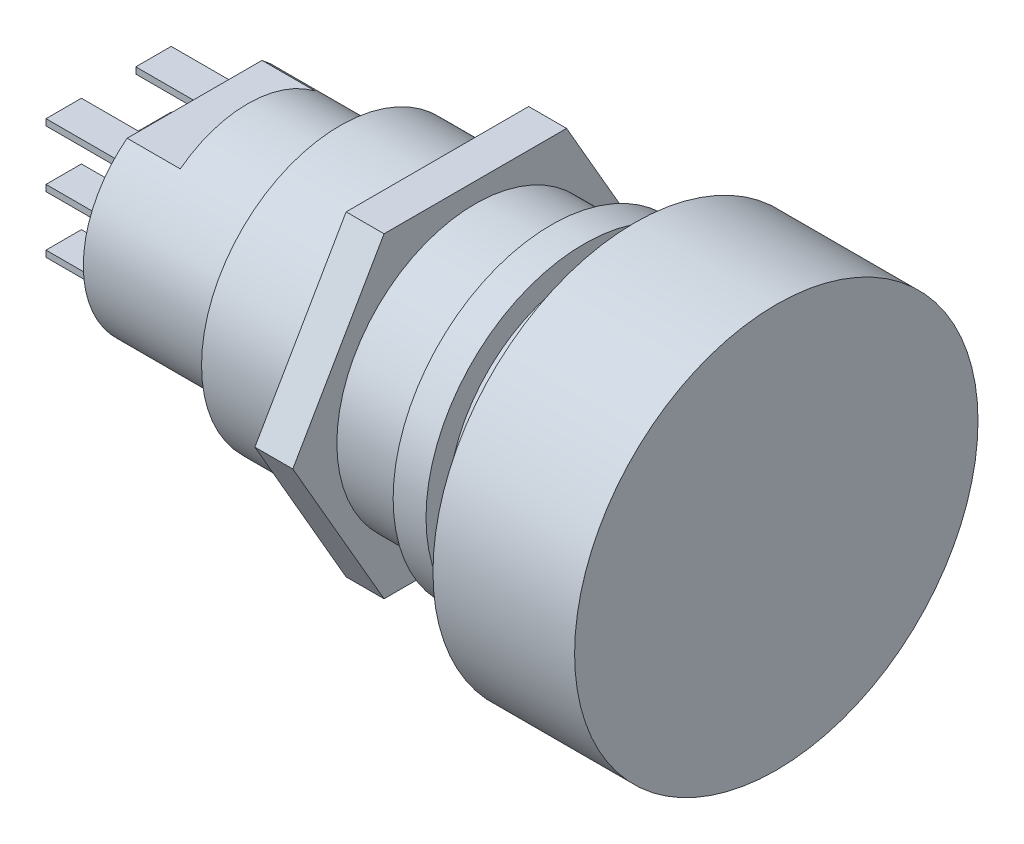
SolidWorks part; units mm, degrees
ref_plane "Plan de face" through (0, 0, 0) normal (0, 0, 1) x (1, 0, 0)
ref_plane "Plan de dessus" through (0, 0, 0) normal (0, 1, 0) x (1, 0, 0)
ref_plane "Plan de droite" through (0, 0, 0) normal (1, 0, 0) x (0, 0, -1)
sketch "Esquisse2" plane through (0, 0, 0) normal (0, 0, 1) x (1, 0, 0)
  line L0 (-7.1166, 11.1773) -> (45.3334, 11.1773) construction
  line L1 (0, 10.95) -> (0, 8.8)
  line L2 (34.5, 0) -> (34.5, 15.95)
  line L3 (34.5, 15.95) -> (23.3, 15.95)
  line L4 (23.3, 15.95) -> (23.3, 10.75)
  line L5 (23.3, 10.75) -> (19.3, 10.75)
  line L6 (19.3, 10.75) -> (19.3, 12.5)
  line L7 (19.3, 12.5) -> (16.7, 12.5)
  line L8 (16.7, 12.5) -> (16.7, 10.95)
  line L9 (16.7, 10.95) -> (0, 10.95)
  line L12 (0, 0) -> (34.5, 0)
  line L13 (0, 8.8) -> (-11.5, 8.8)
  line L14 (-11.5, 8.8) -> (-11.5, 0)
  line L15 (0, 0) -> (-11.5, 0)
  dimension "D1" = 15.95
  dimension "D2" = 52.45
  dimension "D3" = 34.5
  dimension "D4" = 4
  dimension "D5" = 10.75
  dimension "D6" = 12.5
  dimension "D7" = 10.95
  dimension "D8" = 16.7
  dimension "D9" = 2.6
  dimension "D10" = 11.5
  dimension "D11" = 8.8
revolve "Révolution1" add sketch "Esquisse2" angle 360 about L12
sketch "Esquisse4" plane through (-11.5, 0, 0) normal (-1, 0, 0) x (0, 0, 1)
  line L0 (0, 0) -> (4.1607, 0) construction
  line L1 (-5.3329, 9.6739) -> (5.3329, 9.6739)
  line L2 (-5.3329, 9.6739) -> (-5.3329, 7)
  line L3 (-5.3329, 7) -> (5.3329, 7)
  line L4 (5.3329, 9.6739) -> (5.3329, 7)
  line L5 (5.3329, -9.6739) -> (5.3329, -7)
  line L6 (-5.3329, -7) -> (5.3329, -7)
  line L7 (-5.3329, -9.6739) -> (-5.3329, -7)
  line L8 (-5.3329, -9.6739) -> (5.3329, -9.6739)
  circle A0 centre (0, 0) radius 8.8 construction
  dimension "D1" = 14
extrude "Enlèv. mat.-Extru.1" cut sketch "Esquisse4" against normal blind 4.2
sketch "Esquisse3" plane through (-11.5, 0, 0) normal (1, 0, 0) x (0, 0, -1)
  line L0 (-81.3989, 11.1206) -> (-28.9489, 11.1206) construction
  line L5 (0, 0) -> (0, 2.3918) construction
  line L6 (4.95, 4.75) -> (2.15, 4.75)
  line L7 (4.95, 4.75) -> (4.95, 4.25)
  line L8 (4.95, 4.25) -> (2.15, 4.25)
  line L9 (2.15, 4.75) -> (2.15, 4.25)
  line L10 (4.95, 0.25) -> (2.15, 0.25)
  line L11 (4.95, 0.25) -> (4.95, -0.25)
  line L12 (4.95, -0.25) -> (2.15, -0.25)
  line L13 (2.15, 0.25) -> (2.15, -0.25)
  line L14 (0, 0) -> (-1.5478, 0) construction
  line L15 (4.95, -4.25) -> (2.15, -4.25)
  line L16 (2.15, -4.75) -> (2.15, -4.25)
  line L17 (4.95, -4.75) -> (2.15, -4.75)
  line L18 (4.95, -4.75) -> (4.95, -4.25)
  line L19 (-4.95, -0.25) -> (-2.15, -0.25)
  line L20 (-2.15, 0.25) -> (-2.15, -0.25)
  line L21 (-4.95, 0.25) -> (-2.15, 0.25)
  line L22 (-4.95, 0.25) -> (-4.95, -0.25)
  line L23 (-4.95, -4.75) -> (-4.95, -4.25)
  line L24 (-4.95, -4.75) -> (-2.15, -4.75)
  line L25 (-2.15, -4.75) -> (-2.15, -4.25)
  line L26 (-4.95, -4.25) -> (-2.15, -4.25)
  line L27 (-4.95, 4.25) -> (-2.15, 4.25)
  line L28 (-2.15, 4.75) -> (-2.15, 4.25)
  line L29 (-4.95, 4.75) -> (-2.15, 4.75)
  line L30 (-4.95, 4.75) -> (-4.95, 4.25)
  point P36 (3.55, -4.75)
  point P37 (-3.55, -4.75)
  point P38 (4.95, -4.5)
  point P39 (4.95, 0)
  point P41 (2.15, 0)
  dimension "D1" = 52.45
  dimension "D2" = 7.1
  dimension "D3" = 4.5
  dimension "D4" = 0.5
  dimension "D5" = 2.8
extrude "Boss.-Extru.1" add sketch "Esquisse3" against normal blind 6.8
sketch "Esquisse5" plane through (16.7, 0, 0) normal (-1, 0, 0) x (0, 0, 1)
  line L1 (7.2169, 12.5) -> (-7.2169, 12.5)
  line L2 (-7.2169, 12.5) -> (-14.4338, 0)
  line L3 (-14.4338, 0) -> (-7.2169, -12.5)
  line L4 (-7.2169, -12.5) -> (7.2169, -12.5)
  line L5 (7.2169, -12.5) -> (14.4338, 0)
  line L6 (14.4338, 0) -> (7.2169, 12.5)
  circle A0 centre (0, 0) radius 10.95 construction
  circle A1 centre (0, 0) radius 10.95
  circle A2 centre (0, 0) radius 12.5 construction
  dimension "D1" = 25
extrude "Boss.-Extru.2" add sketch "Esquisse5" along normal blind 3 from offset 6 separate body
